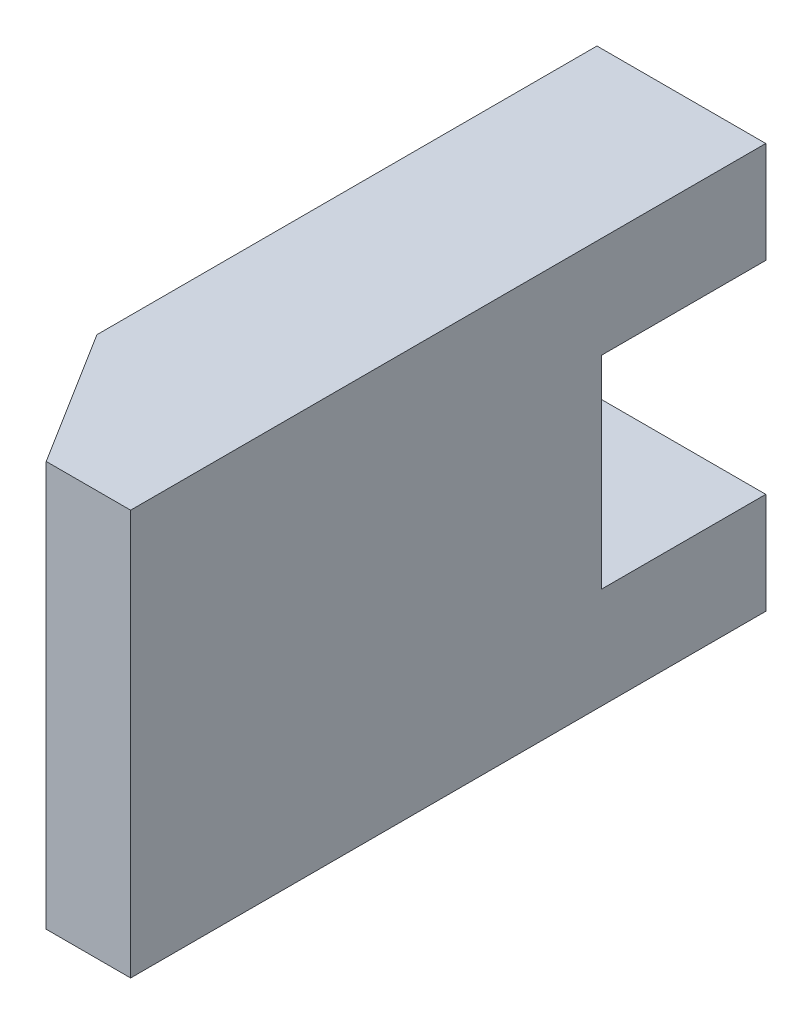
SolidWorks part; units mm, degrees
ref_plane "Front Plane" through (0, 0, 0) normal (0, 0, 1) x (1, 0, 0)
ref_plane "Top Plane" through (0, 0, 0) normal (0, 1, 0) x (1, 0, 0)
ref_plane "Right Plane" through (0, 0, 0) normal (1, 0, 0) x (0, 0, -1)
sketch "Sketch1" plane through (0, 0, 0) normal (1, 0, 0) x (0, 0, -1)
  line L0 (0, 6) -> (0, -6)
  line L1 (0, 6) -> (18.8124, 6)
  line L2 (18.8124, 6) -> (18.8124, 3)
  line L3 (18.8124, 3) -> (13.9501, 3)
  line L4 (13.9501, 3) -> (13.9501, -3)
  line L5 (13.9501, -3) -> (18.8124, -3)
  line L6 (18.8124, -3) -> (18.8124, -6)
  line L7 (18.8124, -6) -> (0, -6)
  point P4 (0, 0)
  dimension "D1" = 12
  dimension "D2" = 6
extrude "Boss-Extrude1" add sketch "Sketch1" along normal blind 5
sketch "Sketch2" plane through (0, 6, 0) normal (0, 1, 0) x (1, 0, 0)
  line L0 (5, 18.8124) -> (5, 0) construction
  line L1 (0, 0) -> (5, 0)
  line L2 (0, 0) -> (0, 4)
  line L3 (0, 4) -> (5, 4)
  line L4 (5, 0) -> (5, 4)
  line L5 (0, 4) -> (2.5, 0)
  line M2 (0, 18.8124) -> (0, 0)
  line M3 (0, 0) -> (5, 0)
  dimension "D1" = 4
extrude "Cut-Extrude1" cut sketch "Sketch2" against normal through all contours L5 M2 M3
